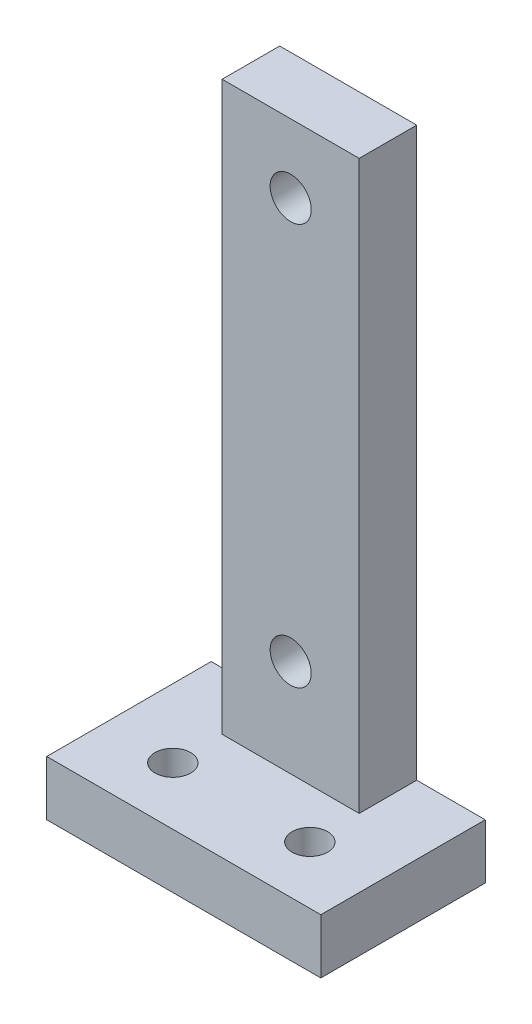
SolidWorks part; units mm, degrees
ref_plane "Front Plane" through (0, 0, 0) normal (0, 0, 1) x (1, 0, 0)
ref_plane "Top Plane" through (0, 0, 0) normal (0, 1, 0) x (1, 0, 0)
ref_plane "Right Plane" through (0, 0, 0) normal (1, 0, 0) x (0, 0, -1)
sketch "Sketch1" plane through (0, 0, 0) normal (0, 1, 0) x (1, 0, 0)
  line L1 (-100.9616, 61.8132) -> (-75.5616, 61.8132)
  line L2 (-100.9616, 61.8132) -> (-100.9616, 46.5732)
  line L3 (-100.9616, 46.5732) -> (-75.5616, 46.5732)
  line L4 (-75.5616, 61.8132) -> (-75.5616, 46.5732)
  dimension "D1" = 25.4
  dimension "D2" = 15.24
extrude "Boss-Extrude1" add sketch "Sketch1" against normal blind 5.08
sketch "Sketch2" plane through (0, 0, 0) normal (0, 1, 0) x (1, 0, 0)
  line L0 (-100.9616, 51.9072) -> (-75.5616, 51.9072) construction
  line L2 (-75.5616, 46.5732) -> (-75.5616, 61.8132) construction
  line L3 (-88.2616, 61.8132) -> (-88.2616, 46.5732) construction
  line L4 (-75.5616, 61.8132) -> (-100.9616, 61.8132) construction
  line L5 (-100.9616, 46.5732) -> (-75.5616, 46.5732) construction
  circle A0 centre (-94.6116, 51.9072) radius 1.651
  circle A1 centre (-81.9116, 51.9072) radius 1.651
  dimension "D1" = 3.302
  dimension "D2" = 12.7
  dimension "D3" = 9.906
extrude "Cut-Extrude1" cut sketch "Sketch2" against normal through all
sketch "Sketch3" plane through (0, 0, 0) normal (0, 1, 0) x (1, 0, 0)
  line L0 (-75.5616, 61.8132) -> (-100.9616, 61.8132) construction
  line L1 (-94.6116, 61.8132) -> (-81.9116, 61.8132)
  line L2 (-94.6116, 61.8132) -> (-94.6116, 56.4792)
  line L3 (-94.6116, 56.4792) -> (-81.9116, 56.4792)
  line L4 (-81.9116, 61.8132) -> (-81.9116, 56.4792)
  line L5 (-94.6116, 61.8132) -> (-100.9616, 61.8132) construction
  line L6 (-81.9116, 61.8132) -> (-75.5616, 61.8132) construction
  dimension "D1" = 5.334
  dimension "D2" = 12.7
extrude "Boss-Extrude2" add sketch "Sketch3" along normal blind 52.578
sketch "Sketch4" plane through (0, 0, -56.4792) normal (0, 0, 1) x (1, 0, 0)
  line L0 (-94.6116, 46.228) -> (-88.2616, 46.228) construction
  line L1 (-94.6116, 52.578) -> (-94.6116, 0) construction
  line L2 (-88.2616, 46.228) -> (-81.9116, 46.228) construction
  line L3 (-81.9116, 52.578) -> (-81.9116, 0) construction
  line L4 (-81.9116, 52.578) -> (-94.6116, 52.578) construction
  circle A0 centre (-88.2616, 46.228) radius 1.905
  circle A1 centre (-88.2616, 9.017) radius 1.905
  point P3 (-88.2616, 52.578)
  dimension "D3" = 3.81
  dimension "D1" = 6.35
  dimension "D2" = 37.211
extrude "Cut-Extrude2" cut sketch "Sketch4" against normal through all
